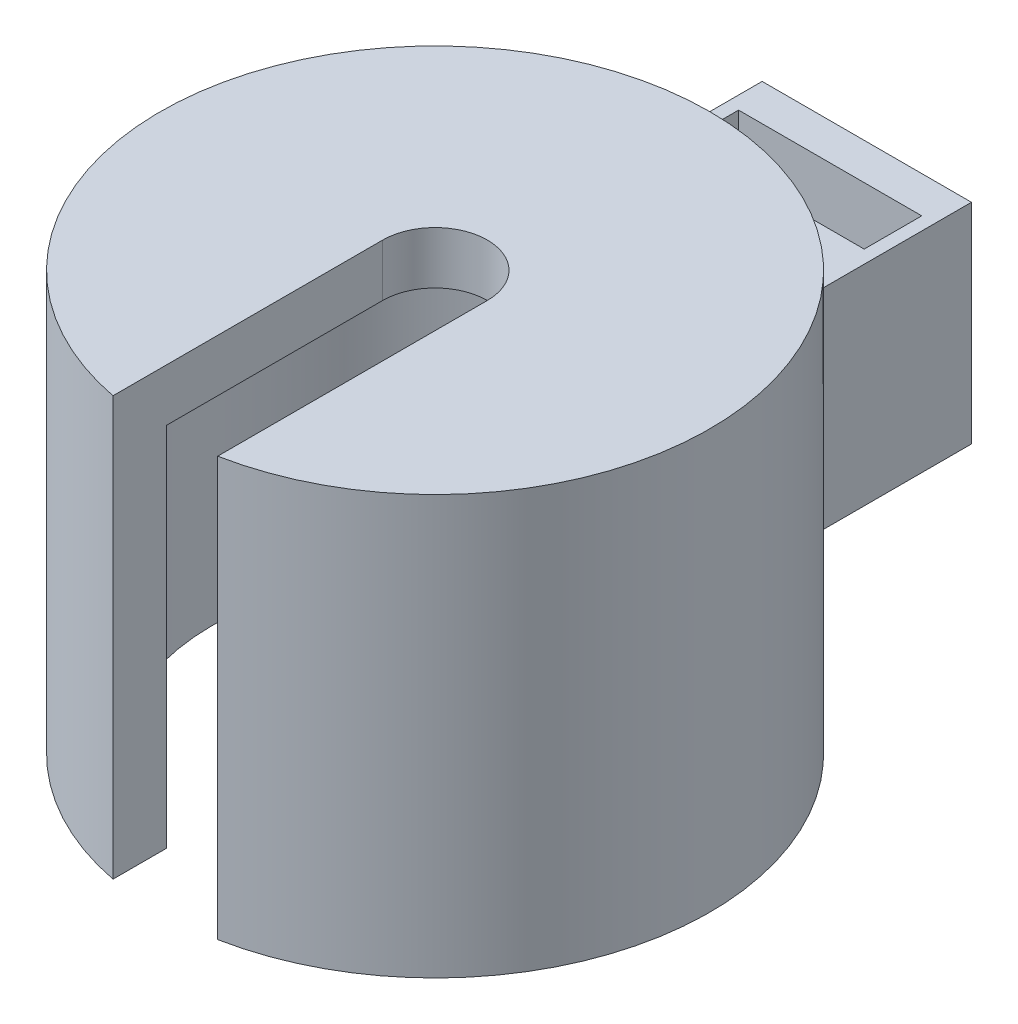
SolidWorks part; units mm, degrees
ref_plane "Front Plane" through (0, 0, 0) normal (0, 0, 1) x (1, 0, 0)
ref_plane "Top Plane" through (0, 0, 0) normal (0, 1, 0) x (1, 0, 0)
ref_plane "Right Plane" through (0, 0, 0) normal (1, 0, 0) x (0, 0, -1)
sketch "Sketch1" plane through (0, 0, 0) normal (0, 1, 0) x (1, 0, 0)
  line L1 (-1, 0) -> (1, 0)
  line L2 (-1, 0) -> (-1, -6.3229)
  line L3 (-1, -6.3229) -> (1, -6.3229)
  line L4 (1, 0) -> (1, -6.3229)
  circle A0 centre (0, 0) radius 4.25
  circle A1 centre (0, 0) radius 5.25
  circle A2 centre (0, 0) radius 1
  dimension "D1" = 8.5
  dimension "D2" = 10.5
  dimension "D3" = 2
  dimension "D4" = 2
extrude "Boss-Extrude1" add sketch "Sketch1" along normal blind 7 contours L4 A1 L2 A0
sketch "Sketch2" plane through (0, 7, 0) normal (0, 1, 0) x (1, 0, 0)
  line L1 (-1, 0) -> (1, 0)
  line L2 (-1, 0) -> (-1, -6.0985)
  line L3 (-1, -6.0985) -> (1, -6.0985)
  line L4 (1, 0) -> (1, -6.0985)
  circle A0 centre (0, 0) radius 5.25
  circle A1 centre (0, 0) radius 1
  line M7 (1, -4.1307) -> (1, -5.1539)
  arc M8 (1, -5.1539) -> (-1, -5.1539) centre (0, 0) ccw
  line M9 (-1, -5.1539) -> (-1, -4.1307)
  arc M10 (-1, -4.1307) -> (1, -4.1307) centre (0, 0) cw
  dimension "D1" = 2
  dimension "D2" = 2
extrude "Boss-Extrude2" add sketch "Sketch2" along normal blind 1 contours A1 L4 L2 M10 | M10 M7 M8 M9
sketch "Sketch3" plane through (0, 0, 0) normal (1, 0, 0) x (0, 0, -1)
  line L0 (5.25, 8) -> (5.25, 6)
  line L1 (5.25, 0) -> (5.25, 8) construction
  line L2 (5.25, 6) -> (4.25, 6)
  line L4 (4.25, 6) -> (8.25, 6)
  line L5 (4.25, 6) -> (4.25, 2)
  line L6 (4.25, 2) -> (8.25, 2)
  line L7 (8.25, 6) -> (8.25, 2)
  dimension "D1" = 2
  dimension "D2" = 1
  dimension "D3" = 4
  dimension "D4" = 4
extrude "Boss-Extrude3" add sketch "Sketch3" along normal blind 2 and the other way blind 2 contours L7 L4 L2 L5 L6
sketch "Sketch4" plane through (0, 6, 0) normal (0, 1, 0) x (1, 0, 0)
  line L0 (0, 8.25) -> (0, 7.55)
  line L1 (-2, 8.25) -> (2, 8.25) construction
  line L2 (0, -4.4) -> (0, 4.4) construction
  line L3 (0, 7.55) -> (1.75, 7.55)
  line L5 (1.75, 7.55) -> (-1.75, 7.55)
  line L6 (1.75, 7.55) -> (1.75, 6.45)
  line L7 (1.75, 6.45) -> (-1.75, 6.45)
  line L8 (-1.75, 7.55) -> (-1.75, 6.45)
  dimension "D1" = 0.7
  dimension "D2" = 1.75
  dimension "D3" = 3.5
  dimension "D4" = 1.1
extrude "Cut-Extrude1" cut sketch "Sketch4" against normal blind 5 contours L5 L8 L7 L6 L3
